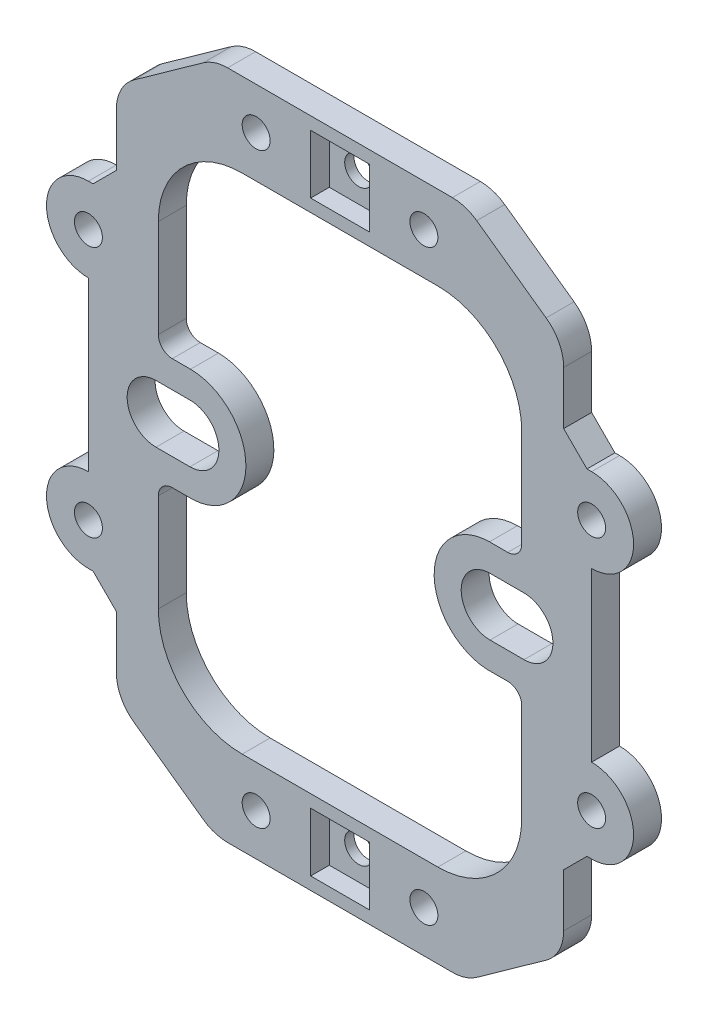
SolidWorks part; units mm, degrees
ref_plane "Alzado" through (0, 0, 0) normal (0, 0, 1) x (1, 0, 0)
ref_plane "Planta" through (0, 0, 0) normal (0, 1, 0) x (1, 0, 0)
ref_plane "Vista lateral" through (0, 0, 0) normal (1, 0, 0) x (0, 0, -1)
sketch "Model" plane through (0, 0, 0) normal (0, 0, 1) x (1, 0, 0)
  line L0 (61.8375, 277.946) -> (61.8375, 283.6296)
  line L1 (25.7796, 221.446) -> (49.8954, 221.446)
  line L2 (49.8954, 293.4454) -> (25.7796, 293.4454)
  line L3 (13.8375, 231.2618) -> (13.8375, 236.946)
  line L4 (15.722, 287.2914) -> (23.1641, 292.6072)
  line L5 (52.511, 292.6072) -> (59.9531, 287.2914)
  line L6 (15.722, 227.6) -> (23.1641, 222.2842)
  line L7 (52.511, 222.2842) -> (59.9531, 227.6)
  line L8 (18.3375, 275.4454) -> (18.3375, 264.9454)
  line L9 (48.3375, 284.4454) -> (27.3375, 284.4454)
  line L10 (57.3375, 264.9454) -> (57.3375, 275.4454)
  line L11 (27.3375, 230.446) -> (48.3375, 230.446)
  line L12 (57.3375, 239.446) -> (57.3375, 249.959)
  line L13 (18.3375, 249.959) -> (18.3375, 239.446)
  line L14 (22.1378, 251.459) -> (19.8375, 251.459)
  line L15 (21.798, 263.4454) -> (19.8375, 263.4454)
  line L16 (55.8375, 263.4454) -> (53.877, 263.4454)
  line L17 (55.8375, 251.459) -> (53.5373, 251.459)
  line L18 (10.8375, 266.446) -> (10.8375, 248.446)
  line L19 (13.8375, 277.946) -> (13.8375, 283.6296)
  line L20 (64.8375, 266.446) -> (64.8375, 248.446)
  line L21 (61.8375, 231.2618) -> (61.8375, 236.946)
  line L22 (11.3375, 275.446) -> (10.8375, 275.446)
  line L23 (64.8375, 275.446) -> (64.3375, 275.446)
  line L24 (64.3375, 239.446) -> (64.8375, 239.446)
  line L25 (10.8375, 239.446) -> (11.3375, 239.446)
  line L26 (13.8375, 277.946) -> (11.3375, 275.446)
  line L27 (64.3375, 275.446) -> (61.8375, 277.946)
  line L28 (64.3375, 239.446) -> (61.8375, 236.946)
  line L29 (11.3375, 239.446) -> (13.8375, 236.946)
  line L30 (18.0923, 260.5454) -> (21.7373, 260.5457)
  line L31 (18.0923, 254.3454) -> (21.7373, 254.3457)
  line L32 (53.9373, 260.5457) -> (57.5823, 260.5454)
  line L33 (53.9373, 254.3457) -> (57.582, 254.3454)
  arc A0 (15.722, 287.2914) -> (13.8375, 283.6296) centre (18.3375, 283.6296) ccw
  arc A1 (25.7796, 293.4454) -> (23.1641, 292.6072) centre (25.7796, 288.9454) ccw
  arc A2 (52.511, 292.6072) -> (49.8954, 293.4454) centre (49.8954, 288.9454) ccw
  arc A3 (61.8375, 283.6296) -> (59.9531, 287.2914) centre (57.3375, 283.6296) ccw
  arc A4 (59.9531, 227.6) -> (61.8375, 231.2618) centre (57.3375, 231.2618) ccw
  arc A5 (49.8954, 221.446) -> (52.511, 222.2842) centre (49.8954, 225.946) ccw
  arc A6 (23.1641, 222.2842) -> (25.7796, 221.446) centre (25.7796, 225.946) ccw
  arc A7 (13.8375, 231.2618) -> (15.722, 227.6) centre (18.3375, 231.2618) ccw
  circle A8 centre (46.8375, 288.946) radius 1.5
  circle A9 centre (28.8375, 288.946) radius 1.5
  circle A10 centre (46.8375, 225.946) radius 1.5
  circle A11 centre (28.8375, 225.946) radius 1.5
  circle A12 centre (37.8375, 288.946) radius 1.5
  circle A13 centre (37.8375, 225.946) radius 1.5
  arc A14 (18.3375, 264.9454) -> (19.8375, 263.4454) centre (19.8375, 264.9454) ccw
  arc A15 (19.8375, 251.459) -> (18.3375, 249.959) centre (19.8375, 249.959) ccw
  arc A16 (57.3375, 249.959) -> (55.8375, 251.459) centre (55.8375, 249.959) ccw
  arc A17 (55.8375, 263.4454) -> (57.3375, 264.9454) centre (55.8375, 264.9454) ccw
  arc A18 (22.1378, 251.459) -> (21.677, 263.4454) centre (21.7375, 257.4457) ccw
  arc A19 (53.998, 263.4454) -> (53.5373, 251.459) centre (53.9375, 257.4457) ccw
  arc A20 (27.3375, 284.4454) -> (18.3375, 275.4454) centre (27.3375, 275.4454) ccw
  arc A21 (57.3375, 275.4454) -> (48.3375, 284.4454) centre (48.3375, 275.4454) ccw
  arc A22 (48.3375, 230.446) -> (57.3375, 239.446) centre (48.3375, 239.446) ccw
  arc A23 (18.3375, 239.446) -> (27.3375, 230.446) centre (27.3375, 239.446) ccw
  circle A24 centre (64.8375, 270.946) radius 1.5
  circle A25 centre (64.8375, 243.946) radius 1.5
  circle A26 centre (10.8375, 270.946) radius 1.5
  circle A27 centre (10.8375, 243.946) radius 1.5
  arc A28 (10.8375, 275.446) -> (10.8375, 266.446) centre (10.8375, 270.946) ccw
  arc A29 (64.8375, 266.446) -> (64.8375, 275.446) centre (64.8375, 270.946) ccw
  arc A30 (64.8375, 239.446) -> (64.8375, 248.446) centre (64.8375, 243.946) ccw
  arc A31 (10.8375, 248.446) -> (10.8375, 239.446) centre (10.8375, 243.946) ccw
  arc A32 (57.582, 254.3454) -> (57.5823, 260.5454) centre (57.5821, 257.4454) ccw
  arc A33 (53.9373, 260.5457) -> (53.9373, 254.3457) centre (53.9373, 257.4457) ccw
  arc A34 (18.0923, 260.5454) -> (18.0923, 254.3454) centre (18.0923, 257.4454) ccw
  arc A35 (21.7373, 254.3457) -> (21.7373, 260.5457) centre (21.7373, 257.4457) ccw
extrude "Saliente-Extruir1" add sketch "Model" along normal blind 3 contours L18 A31 L25 L29 L3 A7 L6 A6 L1 A5 L7 A4 L21 L28 L24 A30 L20 A29 L23 L27 L0 A3 L5 A2 L2 A1 L4 A0 L19 L26 L22 A28 A35 L31 A34 L30 A33 L32 A32 L33 A8 A9 A10 A11
sketch "Croquis1" plane through (0, 0, 3) normal (0, 0, 1) x (1, 0, 0)
  line L1 (34.6875, 285.796) -> (40.9875, 285.796)
  line L2 (34.6875, 285.796) -> (34.6875, 292.096)
  line L3 (34.6875, 292.096) -> (40.9875, 292.096)
  line L4 (40.9875, 285.796) -> (40.9875, 292.096)
  line L5 (34.6875, 285.796) -> (40.9875, 292.096) construction
  line L6 (34.6875, 292.096) -> (40.9875, 285.796) construction
  line L7 (34.6875, 229.096) -> (40.9875, 229.096)
  line L8 (34.6875, 229.096) -> (34.6875, 222.796)
  line L9 (34.6875, 222.796) -> (40.9875, 222.796)
  line L10 (40.9875, 229.096) -> (40.9875, 222.796)
  line L11 (34.6875, 229.096) -> (40.9875, 222.796) construction
  line L12 (34.6875, 222.796) -> (40.9875, 229.096) construction
  point P0 (37.8375, 288.946)
  point P5 (37.8375, 225.946)
extrude "Cortar-Extruir1" cut sketch "Croquis1" against normal blind 2
